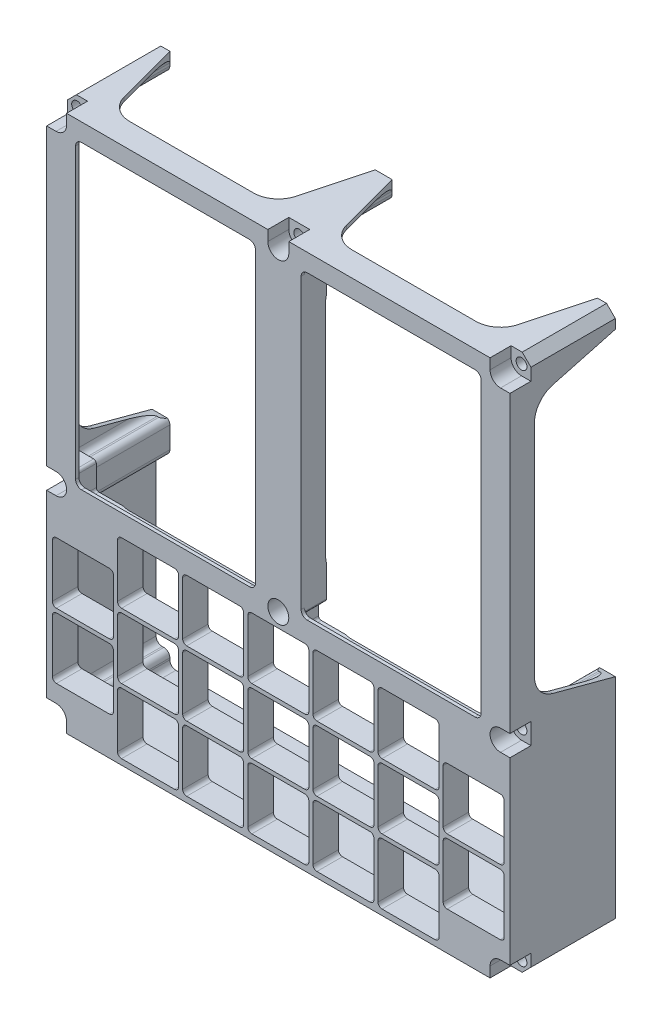
SolidWorks part; units mm, degrees
ref_plane "Front Plane" through (0, 0, 0) normal (0, 0, 1) x (1, 0, 0)
ref_plane "Top Plane" through (0, 0, 0) normal (0, 1, 0) x (1, 0, 0)
ref_plane "Right Plane" through (0, 0, 0) normal (1, 0, 0) x (0, 0, -1)
sketch "Sketch1" plane through (0, 0, 0) normal (0, 0, 1) x (1, 0, 0)
  line L0 (0, 199.898) -> (3.302, 203.2)
  line L1 (3.302, 0) -> (171.958, 0)
  line L2 (0, 3.302) -> (0, 199.898)
  line L3 (3.302, 203.2) -> (171.958, 203.2)
  line L4 (175.26, 3.302) -> (175.26, 199.898)
  line L5 (171.958, 203.2) -> (175.26, 199.898)
  line L6 (171.958, 0) -> (175.26, 3.302)
  line L7 (0, 3.302) -> (3.302, 0)
  line L8 (123.825, 23.749) -> (123.825, 3.683)
  line L9 (76.708, 196.469) -> (13.208, 196.469)
  line L10 (78.994, 194.183) -> (78.994, 84.963)
  line L11 (76.708, 82.677) -> (13.208, 82.677)
  line L12 (10.922, 194.183) -> (10.922, 84.963)
  line L13 (162.052, 196.469) -> (98.552, 196.469)
  line L14 (164.338, 194.183) -> (164.338, 84.963)
  line L15 (162.052, 82.677) -> (98.552, 82.677)
  line L16 (96.266, 194.183) -> (96.266, 84.963)
  line L17 (146.939, 25.273) -> (126.873, 25.273)
  line L18 (148.463, 23.749) -> (148.463, 3.683)
  line L19 (146.939, 2.159) -> (126.873, 2.159)
  line L20 (125.349, 23.749) -> (125.349, 3.683)
  line L21 (122.301, 25.273) -> (102.235, 25.273)
  line L22 (100.711, 23.749) -> (100.711, 3.683)
  line L23 (122.301, 2.159) -> (102.235, 2.159)
  line L24 (99.187, 23.749) -> (99.187, 3.683)
  line L25 (97.663, 25.273) -> (77.597, 25.273)
  line L26 (76.073, 23.749) -> (76.073, 3.683)
  line L27 (97.663, 2.159) -> (77.597, 2.159)
  line L28 (74.549, 23.749) -> (74.549, 3.683)
  line L29 (73.025, 25.273) -> (52.959, 25.273)
  line L30 (51.435, 23.749) -> (51.435, 3.683)
  line L31 (73.025, 2.159) -> (52.959, 2.159)
  line L32 (49.911, 23.749) -> (49.911, 3.683)
  line L33 (48.387, 25.273) -> (28.321, 25.273)
  line L34 (26.797, 23.749) -> (26.797, 3.683)
  line L35 (48.387, 2.159) -> (28.321, 2.159)
  line L36 (123.825, 48.387) -> (123.825, 28.321)
  line L37 (122.301, 49.911) -> (102.235, 49.911)
  line L38 (100.711, 48.387) -> (100.711, 28.321)
  line L39 (122.301, 26.797) -> (102.235, 26.797)
  line L40 (99.187, 48.387) -> (99.187, 28.321)
  line L41 (97.663, 49.911) -> (77.597, 49.911)
  line L42 (76.073, 48.387) -> (76.073, 28.321)
  line L43 (97.663, 26.797) -> (77.597, 26.797)
  line L44 (74.549, 48.387) -> (74.549, 28.321)
  line L45 (73.025, 49.911) -> (52.959, 49.911)
  line L46 (51.435, 48.387) -> (51.435, 28.321)
  line L47 (73.025, 26.797) -> (52.959, 26.797)
  line L48 (49.911, 48.387) -> (49.911, 28.321)
  line L49 (48.387, 49.911) -> (28.321, 49.911)
  line L50 (26.797, 48.387) -> (26.797, 28.321)
  line L51 (48.387, 26.797) -> (28.321, 26.797)
  line L52 (123.825, 73.025) -> (123.825, 52.959)
  line L53 (122.301, 74.549) -> (102.235, 74.549)
  line L54 (100.711, 73.025) -> (100.711, 52.959)
  line L55 (122.301, 51.435) -> (102.235, 51.435)
  line L56 (99.187, 73.025) -> (99.187, 52.959)
  line L57 (97.663, 74.549) -> (77.597, 74.549)
  line L58 (76.073, 73.025) -> (76.073, 52.959)
  line L59 (97.663, 51.435) -> (77.597, 51.435)
  line L60 (74.549, 73.025) -> (74.549, 52.959)
  line L61 (73.025, 74.549) -> (52.959, 74.549)
  line L62 (51.435, 73.025) -> (51.435, 52.959)
  line L63 (73.025, 51.435) -> (52.959, 51.435)
  line L64 (49.911, 73.025) -> (49.911, 52.959)
  line L65 (48.387, 74.549) -> (28.321, 74.549)
  line L66 (26.797, 73.025) -> (26.797, 52.959)
  line L67 (48.387, 51.435) -> (28.321, 51.435)
  line L68 (148.463, 48.387) -> (148.463, 28.321)
  line L69 (146.939, 49.911) -> (126.873, 49.911)
  line L70 (125.349, 48.387) -> (125.349, 28.321)
  line L71 (146.939, 26.797) -> (126.873, 26.797)
  line L72 (148.463, 73.025) -> (148.463, 52.959)
  line L73 (146.939, 74.549) -> (126.873, 74.549)
  line L74 (125.349, 73.025) -> (125.349, 52.959)
  line L75 (146.939, 51.435) -> (126.873, 51.435)
  line L76 (173.101, 36.068) -> (173.101, 16.002)
  line L77 (23.749, 37.592) -> (3.683, 37.592)
  line L78 (25.273, 36.068) -> (25.273, 16.002)
  line L79 (23.749, 14.478) -> (3.683, 14.478)
  line L80 (2.159, 36.068) -> (2.159, 16.002)
  line L81 (171.577, 37.592) -> (151.511, 37.592)
  line L82 (149.987, 36.068) -> (149.987, 16.002)
  line L83 (171.577, 14.478) -> (151.511, 14.478)
  line L84 (173.101, 60.706) -> (173.101, 40.64)
  line L85 (171.577, 62.23) -> (151.511, 62.23)
  line L86 (149.987, 60.706) -> (149.987, 40.64)
  line L87 (171.577, 39.116) -> (151.511, 39.116)
  line L88 (25.273, 60.706) -> (25.273, 40.64)
  line L89 (23.749, 62.23) -> (3.683, 62.23)
  line L90 (2.159, 60.706) -> (2.159, 40.64)
  line L91 (23.749, 39.116) -> (3.683, 39.116)
  circle A0 centre (171.704, 3.937) radius 2.0447
  arc A1 (148.463, 3.683) -> (146.939, 2.159) centre (146.939, 3.683) cw
  arc A2 (126.873, 2.159) -> (125.349, 3.683) centre (126.873, 3.683) cw
  arc A3 (126.873, 25.273) -> (125.349, 23.749) centre (126.873, 23.749) ccw
  arc A4 (146.939, 25.273) -> (148.463, 23.749) centre (146.939, 23.749) cw
  circle A5 centre (171.704, 199.263) radius 2.0447
  circle A6 centre (87.63, 199.263) radius 2.0447
  circle A7 centre (3.556, 199.263) radius 2.0447
  circle A8 centre (3.556, 3.937) radius 2.0447
  circle A9 centre (171.704, 79.883) radius 2.0447
  circle A10 centre (87.63, 79.883) radius 2.0447
  circle A11 centre (3.556, 79.883) radius 2.0447
  arc A12 (98.552, 196.469) -> (96.266, 194.183) centre (98.552, 194.183) ccw
  arc A13 (162.052, 196.469) -> (164.338, 194.183) centre (162.052, 194.183) cw
  arc A14 (76.708, 196.469) -> (78.994, 194.183) centre (76.708, 194.183) cw
  arc A15 (13.208, 196.469) -> (10.922, 194.183) centre (13.208, 194.183) ccw
  arc A16 (164.338, 84.963) -> (162.052, 82.677) centre (162.052, 84.963) cw
  arc A17 (13.208, 82.677) -> (10.922, 84.963) centre (13.208, 84.963) cw
  arc A18 (78.994, 84.963) -> (76.708, 82.677) centre (76.708, 84.963) cw
  arc A19 (98.552, 82.677) -> (96.266, 84.963) centre (98.552, 84.963) cw
  arc A20 (122.301, 25.273) -> (123.825, 23.749) centre (122.301, 23.749) cw
  arc A21 (123.825, 3.683) -> (122.301, 2.159) centre (122.301, 3.683) cw
  arc A22 (102.235, 25.273) -> (100.711, 23.749) centre (102.235, 23.749) ccw
  arc A23 (102.235, 2.159) -> (100.711, 3.683) centre (102.235, 3.683) cw
  arc A24 (97.663, 25.273) -> (99.187, 23.749) centre (97.663, 23.749) cw
  arc A25 (99.187, 3.683) -> (97.663, 2.159) centre (97.663, 3.683) cw
  arc A26 (77.597, 25.273) -> (76.073, 23.749) centre (77.597, 23.749) ccw
  arc A27 (77.597, 2.159) -> (76.073, 3.683) centre (77.597, 3.683) cw
  arc A28 (73.025, 25.273) -> (74.549, 23.749) centre (73.025, 23.749) cw
  arc A29 (74.549, 3.683) -> (73.025, 2.159) centre (73.025, 3.683) cw
  arc A30 (52.959, 25.273) -> (51.435, 23.749) centre (52.959, 23.749) ccw
  arc A31 (52.959, 2.159) -> (51.435, 3.683) centre (52.959, 3.683) cw
  arc A32 (48.387, 25.273) -> (49.911, 23.749) centre (48.387, 23.749) cw
  arc A33 (49.911, 3.683) -> (48.387, 2.159) centre (48.387, 3.683) cw
  arc A34 (28.321, 25.273) -> (26.797, 23.749) centre (28.321, 23.749) ccw
  arc A35 (28.321, 2.159) -> (26.797, 3.683) centre (28.321, 3.683) cw
  arc A36 (122.301, 49.911) -> (123.825, 48.387) centre (122.301, 48.387) cw
  arc A37 (123.825, 28.321) -> (122.301, 26.797) centre (122.301, 28.321) cw
  arc A38 (102.235, 49.911) -> (100.711, 48.387) centre (102.235, 48.387) ccw
  arc A39 (102.235, 26.797) -> (100.711, 28.321) centre (102.235, 28.321) cw
  arc A40 (97.663, 49.911) -> (99.187, 48.387) centre (97.663, 48.387) cw
  arc A41 (99.187, 28.321) -> (97.663, 26.797) centre (97.663, 28.321) cw
  arc A42 (77.597, 49.911) -> (76.073, 48.387) centre (77.597, 48.387) ccw
  arc A43 (77.597, 26.797) -> (76.073, 28.321) centre (77.597, 28.321) cw
  arc A44 (73.025, 49.911) -> (74.549, 48.387) centre (73.025, 48.387) cw
  arc A45 (74.549, 28.321) -> (73.025, 26.797) centre (73.025, 28.321) cw
  arc A46 (52.959, 49.911) -> (51.435, 48.387) centre (52.959, 48.387) ccw
  arc A47 (52.959, 26.797) -> (51.435, 28.321) centre (52.959, 28.321) cw
  arc A48 (48.387, 49.911) -> (49.911, 48.387) centre (48.387, 48.387) cw
  arc A49 (49.911, 28.321) -> (48.387, 26.797) centre (48.387, 28.321) cw
  arc A50 (28.321, 49.911) -> (26.797, 48.387) centre (28.321, 48.387) ccw
  arc A51 (28.321, 26.797) -> (26.797, 28.321) centre (28.321, 28.321) cw
  arc A52 (122.301, 74.549) -> (123.825, 73.025) centre (122.301, 73.025) cw
  arc A53 (123.825, 52.959) -> (122.301, 51.435) centre (122.301, 52.959) cw
  arc A54 (102.235, 74.549) -> (100.711, 73.025) centre (102.235, 73.025) ccw
  arc A55 (102.235, 51.435) -> (100.711, 52.959) centre (102.235, 52.959) cw
  arc A56 (97.663, 74.549) -> (99.187, 73.025) centre (97.663, 73.025) cw
  arc A57 (99.187, 52.959) -> (97.663, 51.435) centre (97.663, 52.959) cw
  arc A58 (77.597, 74.549) -> (76.073, 73.025) centre (77.597, 73.025) ccw
  arc A59 (77.597, 51.435) -> (76.073, 52.959) centre (77.597, 52.959) cw
  arc A60 (73.025, 74.549) -> (74.549, 73.025) centre (73.025, 73.025) cw
  arc A61 (74.549, 52.959) -> (73.025, 51.435) centre (73.025, 52.959) cw
  arc A62 (52.959, 74.549) -> (51.435, 73.025) centre (52.959, 73.025) ccw
  arc A63 (52.959, 51.435) -> (51.435, 52.959) centre (52.959, 52.959) cw
  arc A64 (48.387, 74.549) -> (49.911, 73.025) centre (48.387, 73.025) cw
  arc A65 (49.911, 52.959) -> (48.387, 51.435) centre (48.387, 52.959) cw
  arc A66 (28.321, 74.549) -> (26.797, 73.025) centre (28.321, 73.025) ccw
  arc A67 (28.321, 51.435) -> (26.797, 52.959) centre (28.321, 52.959) cw
  arc A68 (146.939, 49.911) -> (148.463, 48.387) centre (146.939, 48.387) cw
  arc A69 (148.463, 28.321) -> (146.939, 26.797) centre (146.939, 28.321) cw
  arc A70 (126.873, 49.911) -> (125.349, 48.387) centre (126.873, 48.387) ccw
  arc A71 (126.873, 26.797) -> (125.349, 28.321) centre (126.873, 28.321) cw
  arc A72 (146.939, 74.549) -> (148.463, 73.025) centre (146.939, 73.025) cw
  arc A73 (148.463, 52.959) -> (146.939, 51.435) centre (146.939, 52.959) cw
  arc A74 (126.873, 74.549) -> (125.349, 73.025) centre (126.873, 73.025) ccw
  arc A75 (126.873, 51.435) -> (125.349, 52.959) centre (126.873, 52.959) cw
  arc A76 (25.273, 16.002) -> (23.749, 14.478) centre (23.749, 16.002) cw
  arc A77 (3.683, 14.478) -> (2.159, 16.002) centre (3.683, 16.002) cw
  arc A78 (3.683, 37.592) -> (2.159, 36.068) centre (3.683, 36.068) ccw
  arc A79 (23.749, 37.592) -> (25.273, 36.068) centre (23.749, 36.068) cw
  arc A80 (171.577, 37.592) -> (173.101, 36.068) centre (171.577, 36.068) cw
  arc A81 (173.101, 16.002) -> (171.577, 14.478) centre (171.577, 16.002) cw
  arc A82 (151.511, 37.592) -> (149.987, 36.068) centre (151.511, 36.068) ccw
  arc A83 (151.511, 14.478) -> (149.987, 16.002) centre (151.511, 16.002) cw
  arc A84 (171.577, 62.23) -> (173.101, 60.706) centre (171.577, 60.706) cw
  arc A85 (173.101, 40.64) -> (171.577, 39.116) centre (171.577, 40.64) cw
  arc A86 (151.511, 62.23) -> (149.987, 60.706) centre (151.511, 60.706) ccw
  arc A87 (151.511, 39.116) -> (149.987, 40.64) centre (151.511, 40.64) cw
  arc A88 (23.749, 62.23) -> (25.273, 60.706) centre (23.749, 60.706) cw
  arc A89 (25.273, 40.64) -> (23.749, 39.116) centre (23.749, 40.64) cw
  arc A90 (3.683, 62.23) -> (2.159, 60.706) centre (3.683, 60.706) ccw
  arc A91 (3.683, 39.116) -> (2.159, 40.64) centre (3.683, 40.64) cw
  point P0 (0, 0)
  point P1 (175.26, 203.2)
  point P2 (0, 203.2)
  point P3 (175.26, 0)
  point P32 (125.349, 2.159)
  point P35 (125.349, 25.273)
  point P38 (148.463, 25.273)
  point P69 (87.63, 203.2)
  point P72 (96.266, 196.469)
  point P75 (164.338, 196.469)
  point P82 (164.338, 82.677)
  point P251 (2.159, 37.592)
  point P254 (25.273, 37.592)
  dimension "D13" = 4.0894
  dimension "D14" = 1.524
  dimension "D25" = 2.286
  dimension "D33" = 1.524
  dimension "D1" = 203.2
  dimension "D2" = 175.26
  dimension "D3" = 3.302
  dimension "D4" = 45
  dimension "D5" = 3.302
  dimension "D6" = 45
  dimension "D7" = 3.302
  dimension "D8" = 45
  dimension "D9" = 3.302
  dimension "D10" = 45
  dimension "D11" = 23.114
  dimension "D12" = 23.114
  dimension "D15" = 3.556
  dimension "D16" = 3.937
  dimension "D17" = 168.148
  dimension "D18" = 75.946
  dimension "D19" = 119.38
  dimension "D20" = 68.072
  dimension "D21" = 113.792
  dimension "D22" = 7.366
  dimension "D23" = 7.366
  dimension "D24" = 2.794
  dimension "D26" = 23.241
  dimension "D27" = 54.61
  dimension "D30" = 1.524
  dimension "D31" = 1.524
  dimension "D32" = 23.114
  dimension "D34" = 42.291
  dimension "D35" = 1.397
  dimension "D36" = 2
  dimension "D38" = 1.524
  dimension "D39" = 17.653
  dimension "D28" = 5
  dimension "D29" = 3
  dimension "D37" = 2
extrude "Main ouline and through holes" add sketch "Sketch1" along normal blind 39.8653
sketch "Sketch2" plane through (0, 0, 39.8653) normal (0, 0, 1) x (1, 0, 0)
  line L0 (0, 83.8454) -> (3.556, 83.8454)
  line L1 (0, 199.898) -> (0, 3.302) construction
  line L2 (0, 75.9206) -> (3.556, 75.9206)
  line L3 (7.5184, 203.2) -> (7.5184, 199.263)
  line L4 (171.958, 203.2) -> (3.302, 203.2) construction
  line L5 (0, 195.3006) -> (3.556, 195.3006)
  line L6 (7.5184, 203.2) -> (0, 203.2)
  line L7 (0, 203.2) -> (0, 195.3006)
  line L8 (0, 83.8454) -> (0, 75.9206)
  line L9 (0, 7.8994) -> (3.556, 7.8994)
  line L10 (7.5184, 0) -> (7.5184, 3.937)
  line L11 (3.302, 0) -> (171.958, 0) construction
  line L12 (0, 7.8994) -> (0, 0)
  line L13 (0, 0) -> (7.5184, 0)
  line L14 (87.63, 211.8482) -> (87.63, -16.7526) construction
  line L15 (175.26, 0) -> (167.7416, 0)
  line L16 (175.26, 7.8994) -> (175.26, 0)
  line L17 (167.7416, 0) -> (167.7416, 3.937)
  line L18 (175.26, 7.8994) -> (171.704, 7.8994)
  line L19 (175.26, 203.2) -> (175.26, 195.3006)
  line L20 (167.7416, 203.2) -> (175.26, 203.2)
  line L21 (175.26, 195.3006) -> (171.704, 195.3006)
  line L22 (167.7416, 203.2) -> (167.7416, 199.263)
  line L23 (175.26, 83.8454) -> (175.26, 75.9206)
  line L24 (175.26, 75.9206) -> (171.704, 75.9206)
  line L25 (175.26, 83.8454) -> (171.704, 83.8454)
  line L26 (83.6676, 203.2) -> (83.6676, 199.263)
  line L27 (91.5924, 203.2) -> (91.5924, 199.263)
  line L28 (175.26, 3.302) -> (175.26, 199.898) construction
  line L29 (83.6676, 203.2) -> (91.5924, 203.2)
  arc A0 (3.556, 75.9206) -> (3.556, 83.8454) centre (3.556, 79.883) ccw
  arc A1 (7.5184, 199.263) -> (3.556, 195.3006) centre (3.556, 199.263) cw
  circle A2 centre (3.556, 199.263) radius 2.0447 construction
  arc A3 (3.556, 7.8994) -> (7.5184, 3.937) centre (3.556, 3.937) cw
  circle A4 centre (3.556, 3.937) radius 2.0447 construction
  arc A5 (171.704, 7.8994) -> (167.7416, 3.937) centre (171.704, 3.937) ccw
  arc A6 (167.7416, 199.263) -> (171.704, 195.3006) centre (171.704, 199.263) ccw
  arc A7 (171.704, 75.9206) -> (171.704, 83.8454) centre (171.704, 79.883) cw
  circle A8 centre (87.63, 79.883) radius 3.9624
  arc A9 (91.5924, 199.263) -> (83.6676, 199.263) centre (87.63, 199.263) cw
  circle A10 centre (87.63, 199.263) radius 2.0447 construction
  dimension "D1" = 3.9624
  dimension "D2" = 3.9624
  dimension "D3" = 3.9624
  dimension "D4" = 7.9248
  dimension "D5" = 3.9624
extrude "Front holes fillet" cut sketch "Sketch2" against normal blind 7.9375
sketch "Sketch3" plane through (175.26, 0, 0) normal (1, 0, 0) x (0, 0, -1)
  line L0 (0, 196.342) -> (-23.6414, 190.0073)
  line L1 (0, 3.302) -> (0, 199.898) construction
  line L2 (-30.607, 180.9295) -> (-30.607, 97.9625)
  line L3 (-23.6414, 88.8847) -> (0, 82.55)
  line L4 (0, 196.342) -> (40.4314, 196.342) construction
  line L5 (0, 82.55) -> (40.4314, 82.55) construction
  arc A0 (-30.607, 97.9625) -> (-23.6414, 88.8847) centre (-21.209, 97.9625) ccw
  arc A1 (-23.6414, 190.0073) -> (-30.607, 180.9295) centre (-21.209, 180.9295) ccw
  dimension "D4" = 9.398
  dimension "D1" = 15
  dimension "D2" = 15
  dimension "D3" = 30.607
  dimension "D5" = 113.792
  dimension "D6" = 6.858
extrude "Side Cut" cut sketch "Sketch3" against normal through all and the other way through all
sketch "Sketch5" plane through (0, 0, 0) normal (0, 0, -1) x (-1, 0, 0)
  line L0 (-171.704, 79.883) -> (-171.704, 73.533) construction
  line L1 (-3.556, 79.883) -> (-3.556, 73.533) construction
  circle A0 centre (-171.704, 73.533) radius 1.5831
  circle A1 centre (-171.704, 79.883) radius 2.0447 construction
  circle A2 centre (-3.556, 73.533) radius 1.5831
  circle A3 centre (-3.556, 79.883) radius 2.0447 construction
  dimension "D1" = 3.1661
  dimension "D2" = 6.35
  dimension "D3" = 3.1661
  dimension "D4" = 6.35
extrude "Cut-Extrude4" cut sketch "Sketch5" against normal blind 5.08
sketch "Sketch4" plane through (0, 203.2, 0) normal (0, 1, 0) x (1, 0, 0)
  line L0 (87.63, 0) -> (87.63, -63.7959) construction
  line L1 (171.958, 0) -> (3.302, 0) construction
  line L2 (6.731, 0) -> (13.0657, -23.6414)
  line L3 (22.1435, -30.607) -> (69.0425, -30.607)
  line L4 (78.1203, -23.6414) -> (84.455, 0)
  line L5 (6.731, 0) -> (6.731, 22.068) construction
  line L6 (84.455, 0) -> (84.455, 25.4206) construction
  line L7 (0, -31.9278) -> (0, 0) construction
  line L8 (6.731, 0) -> (84.455, 0)
  line L9 (168.529, 0) -> (162.1943, -23.6414)
  line L10 (153.1165, -30.607) -> (106.2175, -30.607)
  line L11 (97.1397, -23.6414) -> (90.805, 0)
  line L12 (168.529, 0) -> (90.805, 0)
  arc A0 (69.0425, -30.607) -> (78.1203, -23.6414) centre (69.0425, -21.209) ccw
  arc A1 (13.0657, -23.6414) -> (22.1435, -30.607) centre (22.1435, -21.209) ccw
  arc A2 (162.1943, -23.6414) -> (153.1165, -30.607) centre (153.1165, -21.209) cw
  arc A3 (106.2175, -30.607) -> (97.1397, -23.6414) centre (106.2175, -21.209) cw
  dimension "D1" = 9.398
  dimension "D2" = 15
  dimension "D3" = 15
  dimension "D4" = 30.607
  dimension "D5" = 6.731
  dimension "D6" = 3.175
extrude "Top Cut" cut sketch "Sketch4" against normal up to surface (128.651 mm away) up to face at (87.63, 74.549, 19.9326)
sketch "Sketch6" plane through (0, 0, 0) normal (0, 0, -1) x (-1, 0, 0)
  line L0 (-94.1837, 201.676) -> (-165.1503, 201.676)
  line L1 (-173.736, 192.7093) -> (-173.736, 86.4367)
  line L2 (-165.1503, 75.565) -> (-94.1837, 75.565)
  line L5 (-175.26, 180.9295) -> (-175.26, 97.9625) construction
  line L7 (-106.2175, 203.2) -> (-153.1165, 203.2) construction
  line L8 (-166.1414, 200.6849) -> (-166.1414, 194.6915)
  line L9 (-96.266, 195.4779) -> (-96.266, 83.6681)
  line L10 (-167.1325, 193.7004) -> (-172.7449, 193.7004)
  line L11 (-172.7449, 85.4456) -> (-167.1325, 85.4456)
  line L12 (-166.1414, 84.4545) -> (-166.1414, 76.5561)
  line L13 (-95.2749, 82.677) -> (-94.1837, 82.677)
  line L14 (-95.2749, 196.469) -> (-94.1837, 196.469)
  line L15 (-93.1926, 197.4601) -> (-93.1926, 200.6849)
  line L16 (-93.1926, 81.6859) -> (-93.1926, 76.5561)
  line L17 (-96.266, 97.9625) -> (-96.266, 180.9295) construction
  line L18 (-153.1165, 196.469) -> (-106.2175, 196.469) construction
  line L19 (-106.2175, 82.677) -> (-153.1165, 82.677) construction
  line L20 (-87.63, 203.2) -> (-87.63, 55.0134) construction
  line L21 (-90.805, 203.2) -> (-84.455, 203.2) construction
  line L22 (-82.0674, 81.6859) -> (-82.0674, 76.5561)
  line L23 (-82.0674, 197.4601) -> (-82.0674, 200.6849)
  line L24 (-79.9851, 196.469) -> (-81.0763, 196.469)
  line L25 (-79.9851, 82.677) -> (-81.0763, 82.677)
  line L26 (-9.1186, 84.4545) -> (-9.1186, 76.5561)
  line L27 (-2.5151, 85.4456) -> (-8.1275, 85.4456)
  line L28 (-8.1275, 193.7004) -> (-2.5151, 193.7004)
  line L29 (-78.994, 195.4779) -> (-78.994, 83.6681)
  line L30 (-9.1186, 200.6849) -> (-9.1186, 194.6915)
  line L31 (-10.1097, 75.565) -> (-81.0763, 75.565)
  line L32 (-1.524, 192.7093) -> (-1.524, 86.4367)
  line L33 (-81.0763, 201.676) -> (-10.1097, 201.676)
  line L34 (-87.63, 193.7004) -> (-92.4633, 193.7004)
  line L35 (-94.742, 191.4217) -> (-94.742, 87.7243)
  line L36 (-92.4633, 85.4456) -> (-87.63, 85.4456)
  line L40 (-87.63, 85.4456) -> (-82.7967, 85.4456)
  line L41 (-80.518, 87.7243) -> (-80.518, 191.4217)
  line L42 (-82.7967, 193.7004) -> (-87.63, 193.7004)
  circle A0 centre (-171.704, 199.263) radius 2.0447 construction
  circle A1 centre (-87.63, 79.883) radius 2.0447 construction
  circle A2 centre (-171.704, 73.533) radius 1.5831 construction
  arc A3 (-172.7449, 85.4456) -> (-173.736, 86.4367) centre (-172.7449, 86.4367) cw
  circle A4 centre (-171.704, 79.883) radius 2.0447 construction
  arc A5 (-167.1325, 85.4456) -> (-166.1414, 84.4545) centre (-167.1325, 84.4545) cw
  arc A6 (-166.1414, 76.5561) -> (-165.1503, 75.565) centre (-165.1503, 76.5561) ccw
  arc A7 (-93.1926, 76.5561) -> (-94.1837, 75.565) centre (-94.1837, 76.5561) cw
  arc A8 (-94.1837, 82.677) -> (-93.1926, 81.6859) centre (-94.1837, 81.6859) cw
  arc A9 (-96.266, 83.6681) -> (-95.2749, 82.677) centre (-95.2749, 83.6681) ccw
  arc A10 (-96.266, 195.4779) -> (-95.2749, 196.469) centre (-95.2749, 195.4779) cw
  arc A11 (-94.1837, 196.469) -> (-93.1926, 197.4601) centre (-94.1837, 197.4601) ccw
  arc A12 (-94.1837, 201.676) -> (-93.1926, 200.6849) centre (-94.1837, 200.6849) cw
  arc A13 (-172.7449, 193.7004) -> (-173.736, 192.7093) centre (-172.7449, 192.7093) ccw
  arc A14 (-166.1414, 194.6915) -> (-167.1325, 193.7004) centre (-167.1325, 194.6915) cw
  arc A15 (-166.1414, 200.6849) -> (-165.1503, 201.676) centre (-165.1503, 200.6849) cw
  arc A16 (-9.1186, 200.6849) -> (-10.1097, 201.676) centre (-10.1097, 200.6849) ccw
  arc A17 (-9.1186, 194.6915) -> (-8.1275, 193.7004) centre (-8.1275, 194.6915) ccw
  arc A18 (-2.5151, 193.7004) -> (-1.524, 192.7093) centre (-2.5151, 192.7093) cw
  arc A19 (-81.0763, 201.676) -> (-82.0674, 200.6849) centre (-81.0763, 200.6849) ccw
  arc A20 (-81.0763, 196.469) -> (-82.0674, 197.4601) centre (-81.0763, 197.4601) cw
  arc A21 (-78.994, 195.4779) -> (-79.9851, 196.469) centre (-79.9851, 195.4779) ccw
  arc A22 (-78.994, 83.6681) -> (-79.9851, 82.677) centre (-79.9851, 83.6681) cw
  arc A23 (-81.0763, 82.677) -> (-82.0674, 81.6859) centre (-81.0763, 81.6859) ccw
  arc A24 (-82.0674, 76.5561) -> (-81.0763, 75.565) centre (-81.0763, 76.5561) ccw
  arc A25 (-9.1186, 76.5561) -> (-10.1097, 75.565) centre (-10.1097, 76.5561) cw
  arc A26 (-8.1275, 85.4456) -> (-9.1186, 84.4545) centre (-8.1275, 84.4545) ccw
  arc A27 (-2.5151, 85.4456) -> (-1.524, 86.4367) centre (-2.5151, 86.4367) ccw
  arc A32 (-82.7967, 85.4456) -> (-80.518, 87.7243) centre (-82.7967, 87.7243) ccw
  arc A33 (-94.742, 87.7243) -> (-92.4633, 85.4456) centre (-92.4633, 87.7243) ccw
  arc A34 (-80.518, 191.4217) -> (-82.7967, 193.7004) centre (-82.7967, 191.4217) ccw
  arc A35 (-92.4633, 193.7004) -> (-94.742, 191.4217) centre (-92.4633, 191.4217) ccw
  point P94 (0, 0)
  point P98 (0, 0)
  point P99 (0, 0)
  point P100 (0, 0)
  point P110 (-86.868, 174.7046)
  point P113 (-88.392, 174.7046)
  dimension "D4" = 5.5626
  dimension "D5" = 5.5626
  dimension "D8" = 2.032
  dimension "D6" = 5.5626
  dimension "D7" = 5.5626
  dimension "D9" = 5.5626
  dimension "D2" = 0.9911
  dimension "D14" = 2.2787
  dimension "D1" = 1.524
  dimension "D3" = 1.524
  dimension "D10" = 1.524
  dimension "D11" = 1.524
  dimension "D12" = 1.524
extrude "Cut-Extrude5" cut sketch "Sketch6" against normal offset from surface (38.5953 mm away) 1.27 up to face at (91.5924, 79.883, 39.8653)
sketch "Sketch8" plane through (0, 0, 0) normal (0, 0, -1) x (-1, 0, 0)
  line L0 (-168.529, 72.644) -> (-168.529, 80.772)
  line L1 (-170.815, 83.058) -> (-171.45, 83.058)
  line L2 (-173.736, 85.344) -> (-173.736, 193.802)
  line L3 (-171.45, 196.088) -> (-170.815, 196.088)
  line L4 (-168.529, 198.374) -> (-168.529, 199.39)
  line L5 (-166.243, 201.676) -> (-93.091, 201.676)
  line L6 (-90.805, 199.39) -> (-90.805, 198.374)
  line L7 (-88.519, 196.088) -> (-86.741, 196.088)
  line L8 (-84.455, 198.374) -> (-84.455, 199.39)
  line L9 (-82.169, 201.676) -> (-9.017, 201.676)
  line L10 (-6.731, 199.39) -> (-6.731, 198.374)
  line L11 (-4.445, 196.088) -> (-3.81, 196.088)
  line L12 (-1.524, 193.802) -> (-1.524, 85.344)
  line L13 (-3.81, 83.058) -> (-4.445, 83.058)
  line L15 (-3.81, 6.731) -> (-4.445, 6.731)
  line L16 (-6.731, 4.445) -> (-6.731, 3.81)
  line L17 (-9.017, 1.524) -> (-166.243, 1.524)
  line L18 (-168.529, 3.81) -> (-168.529, 4.445)
  line L19 (-170.815, 6.731) -> (-171.45, 6.731)
  line L20 (-173.736, 9.017) -> (-173.736, 68.072)
  line L21 (-171.45, 70.358) -> (-170.815, 70.358)
  line L22 (-81.0763, 201.676) -> (-10.1097, 201.676) construction
  line L23 (-3.302, 0) -> (-171.958, 0) construction
  line L24 (-6.731, 80.772) -> (-6.731, 72.644)
  line L25 (-4.445, 70.358) -> (-3.81, 70.358)
  line L26 (-1.524, 68.072) -> (-1.524, 9.017)
  line L27 (-173.736, 180.9295) -> (-173.736, 97.9625) construction
  line L28 (-1.524, 192.7093) -> (-1.524, 86.4367) construction
  circle A0 centre (-87.63, 199.263) radius 2.0447 construction
  circle A1 centre (-171.704, 199.263) radius 2.0447 construction
  circle A2 centre (-3.556, 199.263) radius 2.0447 construction
  circle A3 centre (-171.704, 79.883) radius 2.0447 construction
  circle A4 centre (-3.556, 73.533) radius 1.5831 construction
  arc A5 (-93.091, 201.676) -> (-90.805, 199.39) centre (-93.091, 199.39) cw
  arc A6 (-90.805, 198.374) -> (-88.519, 196.088) centre (-88.519, 198.374) ccw
  arc A7 (-86.741, 196.088) -> (-84.455, 198.374) centre (-86.741, 198.374) ccw
  arc A8 (-84.455, 199.39) -> (-82.169, 201.676) centre (-82.169, 199.39) cw
  arc A9 (-9.017, 201.676) -> (-6.731, 199.39) centre (-9.017, 199.39) cw
  arc A10 (-6.731, 198.374) -> (-4.445, 196.088) centre (-4.445, 198.374) ccw
  arc A11 (-3.81, 196.088) -> (-1.524, 193.802) centre (-3.81, 193.802) cw
  arc A12 (-1.524, 85.344) -> (-3.81, 83.058) centre (-3.81, 85.344) cw
  arc A13 (-4.445, 83.058) -> (-6.731, 80.772) centre (-4.445, 80.772) ccw
  arc A14 (-6.731, 72.644) -> (-4.445, 70.358) centre (-4.445, 72.644) ccw
  arc A15 (-3.81, 70.358) -> (-1.524, 68.072) centre (-3.81, 68.072) cw
  arc A16 (-1.524, 9.017) -> (-3.81, 6.731) centre (-3.81, 9.017) cw
  arc A17 (-4.445, 6.731) -> (-6.731, 4.445) centre (-4.445, 4.445) ccw
  arc A18 (-6.731, 3.81) -> (-9.017, 1.524) centre (-9.017, 3.81) cw
  arc A19 (-166.243, 1.524) -> (-168.529, 3.81) centre (-166.243, 3.81) cw
  arc A20 (-168.529, 4.445) -> (-170.815, 6.731) centre (-170.815, 4.445) ccw
  arc A21 (-171.45, 6.731) -> (-173.736, 9.017) centre (-171.45, 9.017) cw
  arc A22 (-173.736, 68.072) -> (-171.45, 70.358) centre (-171.45, 68.072) cw
  arc A23 (-168.529, 72.644) -> (-170.815, 70.358) centre (-170.815, 72.644) cw
  arc A24 (-168.529, 80.772) -> (-170.815, 83.058) centre (-170.815, 80.772) ccw
  arc A25 (-171.45, 83.058) -> (-173.736, 85.344) centre (-171.45, 85.344) cw
  arc A26 (-173.736, 193.802) -> (-171.45, 196.088) centre (-171.45, 193.802) cw
  arc A27 (-170.815, 196.088) -> (-168.529, 198.374) centre (-170.815, 198.374) ccw
  arc A28 (-168.529, 199.39) -> (-166.243, 201.676) centre (-166.243, 199.39) cw
  point P32 (0, 0)
  point P33 (-2.159, 23.1861)
  point P44 (-168.529, 4.1275)
  point P49 (-90.805, 196.088)
  point P52 (-84.455, 196.088)
  point P87 (-168.529, 83.058)
  point P90 (-173.736, 83.058)
  dimension "D2" = 3.175
  dimension "D3" = 3.175
  dimension "D8" = 3.175
  dimension "D9" = 2.286
  dimension "D1" = 6.35
  dimension "D4" = 3.175
  dimension "D5" = 3.175
  dimension "D6" = 3.175
  dimension "D7" = 1.524
extrude "Cut-Extrude6" cut sketch "Sketch8" against normal offset from surface (30.2133 mm away) 9.652 up to face at (91.5924, 79.883, 39.8653)
sketch "Sketch9" plane through (0, 0, 0) normal (0, 0, -1) x (-1, 0, 0)
  line L0 (-25.273, 36.068) -> (-25.273, 16.002) construction
  line L1 (-166.243, 74.549) -> (-152.273, 74.549)
  line L2 (-168.529, 72.263) -> (-168.529, 67.183)
  line L3 (-166.243, 64.897) -> (-152.273, 64.897)
  line L4 (-149.987, 72.263) -> (-149.987, 67.183)
  line L5 (-162.941, 12.573) -> (-152.273, 12.573)
  line L6 (-165.227, 10.287) -> (-165.227, 4.445)
  line L7 (-162.941, 2.159) -> (-152.273, 2.159)
  line L8 (-149.987, 10.287) -> (-149.987, 4.445)
  line L9 (-22.987, 74.549) -> (-9.017, 74.549)
  line L10 (-25.273, 72.263) -> (-25.273, 67.183)
  line L11 (-22.987, 64.897) -> (-9.017, 64.897)
  line L12 (-6.731, 72.263) -> (-6.731, 67.183)
  line L13 (-22.987, 12.573) -> (-12.319, 12.573)
  line L14 (-25.273, 10.287) -> (-25.273, 4.445)
  line L15 (-22.987, 2.159) -> (-12.319, 2.159)
  line L16 (-10.033, 10.287) -> (-10.033, 4.445)
  line L17 (-48.387, 2.159) -> (-28.321, 2.159) construction
  line L18 (-149.987, 40.64) -> (-149.987, 60.706) construction
  line L19 (-146.939, 2.159) -> (-126.873, 2.159) construction
  line L20 (-126.873, 74.549) -> (-146.939, 74.549) construction
  line L21 (-25.273, 60.706) -> (-25.273, 40.64) construction
  arc A0 (-25.273, 4.445) -> (-22.987, 2.159) centre (-22.987, 4.445) ccw
  arc A1 (-12.319, 2.159) -> (-10.033, 4.445) centre (-12.319, 4.445) ccw
  arc A2 (-12.319, 12.573) -> (-10.033, 10.287) centre (-12.319, 10.287) cw
  arc A3 (-22.987, 12.573) -> (-25.273, 10.287) centre (-22.987, 10.287) ccw
  arc A4 (-9.017, 64.897) -> (-6.731, 67.183) centre (-9.017, 67.183) ccw
  arc A5 (-9.017, 74.549) -> (-6.731, 72.263) centre (-9.017, 72.263) cw
  arc A6 (-22.987, 74.549) -> (-25.273, 72.263) centre (-22.987, 72.263) ccw
  arc A7 (-25.273, 67.183) -> (-22.987, 64.897) centre (-22.987, 67.183) ccw
  arc A8 (-152.273, 2.159) -> (-149.987, 4.445) centre (-152.273, 4.445) ccw
  arc A9 (-152.273, 12.573) -> (-149.987, 10.287) centre (-152.273, 10.287) cw
  arc A10 (-165.227, 4.445) -> (-162.941, 2.159) centre (-162.941, 4.445) ccw
  arc A11 (-162.941, 12.573) -> (-165.227, 10.287) centre (-162.941, 10.287) ccw
  arc A12 (-168.529, 67.183) -> (-166.243, 64.897) centre (-166.243, 67.183) ccw
  arc A13 (-166.243, 74.549) -> (-168.529, 72.263) centre (-166.243, 72.263) ccw
  arc A14 (-152.273, 74.549) -> (-149.987, 72.263) centre (-152.273, 72.263) cw
  arc A15 (-152.273, 64.897) -> (-149.987, 67.183) centre (-152.273, 67.183) ccw
  point P32 (-25.273, 2.159)
  point P37 (-10.033, 12.573)
  point P40 (-25.273, 12.573)
  point P53 (-149.987, 12.573)
  point P56 (-165.227, 2.159)
  point P59 (-165.227, 12.573)
  point P62 (-168.529, 64.897)
  point P65 (-168.529, 74.549)
  dimension "D6" = 2.286
  dimension "D1" = 15.24
  dimension "D2" = 15.24
  dimension "D3" = 10.414
  dimension "D4" = 10.414
  dimension "D5" = 9.652
extrude "Cut-Extrude7" cut sketch "Sketch9" against normal offset from surface (38.3413 mm away) 1.524 up to face at (91.5924, 79.883, 39.8653)
ref_plane "Plane1" through (0, 161.798, 0) normal (0, 1, 0) x (1, 0, 0)
fillet "Fillet1" radius 2.286 32 edges at (150.6566, 2.8286, 38.3413) (149.987, 7.366, 38.3413) (150.6566, 11.9034, 38.3413) (157.607, 12.573, 38.3413) (164.5574, 11.9034, 38.3413) (165.227, 7.366, 38.3413) (164.5574, 2.8286, 38.3413) (10.7026, 2.8286, 38.3413) (10.033, 7.366, 38.3413) (10.7026, 11.9034, 38.3413) (17.653, 12.573, 38.3413) (24.6034, 11.9034, 38.3413) (25.273, 7.366, 38.3413) (24.6034, 2.8286, 38.3413) (24.6034, 73.8794, 38.3413) (25.273, 69.723, 38.3413) (24.6034, 65.5666, 38.3413) (16.002, 64.897, 38.3413) (7.4006, 65.5666, 38.3413) (6.731, 69.723, 38.3413) (7.4006, 73.8794, 38.3413) (167.8594, 73.8794, 38.3413) (168.529, 69.723, 38.3413) (167.8594, 65.5666, 38.3413) (159.258, 64.897, 38.3413) (150.6566, 65.5666, 38.3413) (149.987, 69.723, 38.3413) (150.6566, 73.8794, 38.3413) (157.607, 2.159, 38.3413) (17.653, 2.159, 38.3413) (16.002, 74.549, 38.3413) (159.258, 74.549, 38.3413)
